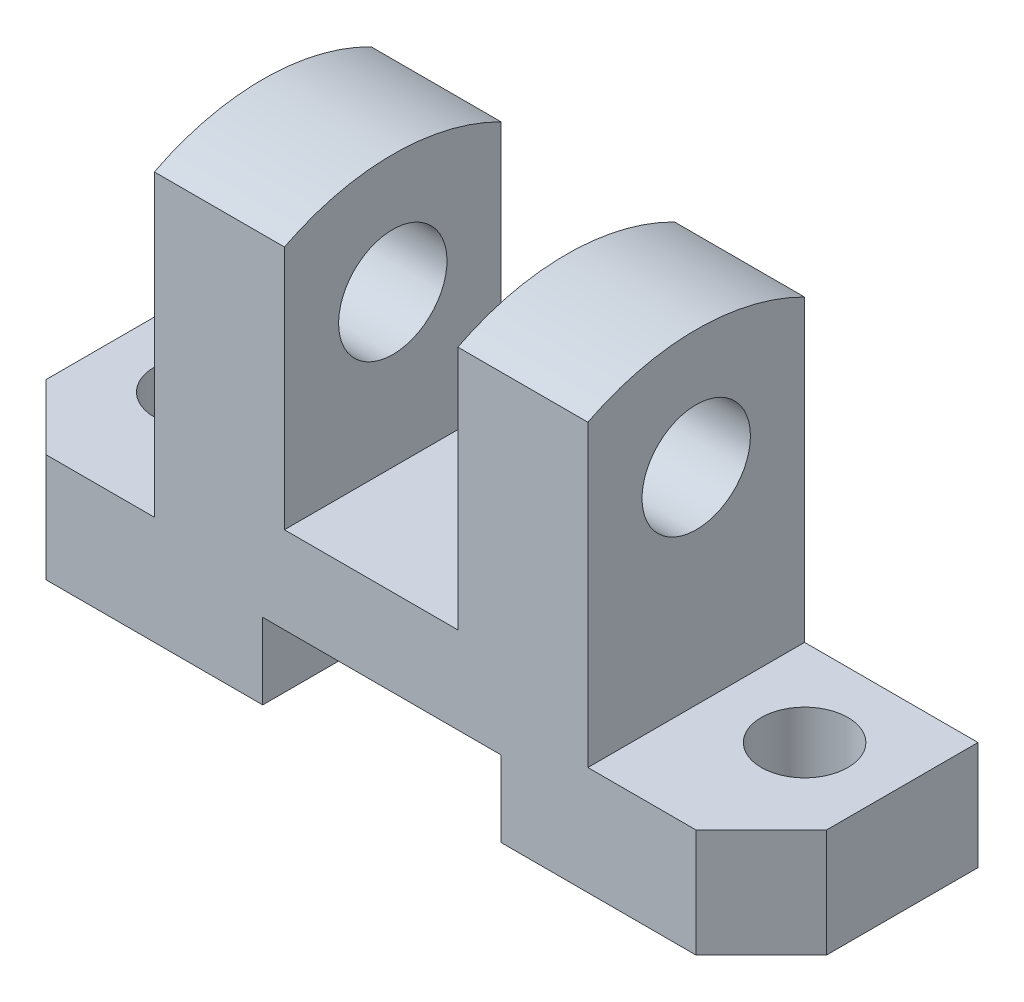
SolidWorks part; units mm, degrees
material "6063-T6"
ref_plane "Plane1" through (0, 0, 0) normal (0, 0, 1) x (1, 0, 0)
ref_plane "Plane2" through (0, 0, 0) normal (0, 1, 0) x (1, 0, 0)
ref_plane "Plane3" through (0, 0, 0) normal (1, 0, 0) x (0, 0, -1)
sketch "Esquisse1" plane through (0, 0, 0) normal (0, 0, 1) x (1, 0, 0)
  line L1 (0, 0) -> (114.3, 0)
  line L2 (0, 0) -> (0, 63.5)
  line L3 (0, 63.5) -> (114.3, 63.5)
  line L4 (114.3, 0) -> (114.3, 63.5)
  dimension "D1" = 114.3
  dimension "D2" = 63.5
extrude "Base-Extrusion" add sketch "Esquisse1" along normal mid plane 31.75
sketch "Esquisse2" plane through (0, 0, 15.875) normal (0, 0, 1) x (1, 0, 0)
  line L0 (114.3, 63.5) -> (0, 63.5) construction
  line L1 (25.4, 63.5) -> (0, 63.5)
  line L2 (25.4, 63.5) -> (25.4, 15.875)
  line L3 (25.4, 15.875) -> (0, 15.875)
  line L4 (0, 63.5) -> (0, 15.875)
  line L5 (0, 63.5) -> (0, 0) construction
  line L6 (0, 0) -> (114.3, 0) construction
  line L7 (114.3, 63.5) -> (88.9, 63.5)
  line L8 (114.3, 63.5) -> (114.3, 15.875)
  line L9 (114.3, 15.875) -> (88.9, 15.875)
  line L10 (88.9, 63.5) -> (88.9, 15.875)
  line L11 (44.45, 63.5) -> (69.85, 63.5)
  line L12 (44.45, 63.5) -> (44.45, 23.8125)
  line L13 (44.45, 23.8125) -> (69.85, 23.8125)
  line L14 (69.85, 63.5) -> (69.85, 23.8125)
  line L15 (41.275, 0) -> (76.2, 0)
  line L16 (41.275, 0) -> (41.275, 11.1125)
  line L17 (41.275, 11.1125) -> (76.2, 11.1125)
  line L18 (76.2, 0) -> (76.2, 11.1125)
  line L19 (114.3, 0) -> (114.3, 63.5) construction
  dimension "D1" = 25.4
  dimension "D2" = 19.05
  dimension "D3" = 25.4
  dimension "D4" = 19.05
  dimension "D5" = 34.925
  dimension "D6" = 11.1125
  dimension "D7" = 12.7
  dimension "D8" = 38.1
  dimension "D9" = 15.875
extrude "Enlèv. mat.-Extru.1" cut sketch "Esquisse2" against normal through all
sketch "Esquisse3" plane through (88.9, 0, 0) normal (1, 0, 0) x (0, 0, -1)
  line L0 (-34.925, 68.575) -> (-34.925, 28.575)
  line L1 (-34.925, 68.575) -> (34.925, 68.575)
  line L2 (34.925, 68.575) -> (34.925, 28.575)
  line L3 (-15.875, 63.5) -> (-15.875, 15.875) construction
  line L4 (15.875, 63.5) -> (-15.875, 63.5) construction
  arc A0 (-34.925, 28.575) -> (34.925, 28.575) centre (0, 28.575) cw
  dimension "D1" = 34.925
  dimension "D2" = 15.875
  dimension "D3" = 34.925
  dimension "D4" = 40
extrude "Enlèv. mat.-Extru.2" cut sketch "Esquisse3" against normal through all
chamfer "Chanfrein1" distance 9.525 angle 45 2 edges at (114.3, 7.9375, 15.875) (0, 7.9375, 15.875)
hole_wizard "Diamètre du perçage 1/2 (0.5)1" positions "Esquisse4" profile "Esquisse5" hole size "1/2" standard "Ansi Inch" end condition through all
sketch "Esquisse4" plane through (0, 15.875, 0) normal (0, 1, 0) x (1, 0, 0)
  line L0 (0, 15.875) -> (25.4, 15.875) construction
  line L1 (114.3, 15.875) -> (114.3, -6.35) construction
  line L2 (0, 15.875) -> (0, -6.35) construction
  point P0 (101.6, 3.175)
  point P2 (12.7, 3.175)
  point P11 (114.3, 4.7625)
  dimension "D1" = 12.7
  dimension "D2" = 12.7
  dimension "D3" = 12.7
sketch "Esquisse5" plane through (101.6, 15.875, -3.175) normal (1, 0, 0) x (0, 0, 1)
  line L0 (0, 0) -> (0, 15.875)
  line L1 (0, 15.875) -> (6.35, 15.875)
  line L2 (6.35, 15.875) -> (6.35, 0)
  line L5 (6.35, 0) -> (0, 0)
  line L11 (0, -6.35) -> (0, 107.95) construction
  dimension "Diamètre du perçage jusqu'au prochain" = 12.7
  dimension "Profondeur du perçage jusqu'au prochain" = 15.875
hole_wizard "Diamètre du perçage 5/8 (0.625)1" positions "Esquisse6" profile "Esquisse7" hole size "5/8" standard "Ansi Inch" end condition through all
sketch "Esquisse6" plane through (88.9, 0, 0) normal (1, 0, 0) x (0, 0, -1)
  line L0 (-6.35, 0) -> (15.875, 0) construction
  point P0 (0, 46.0375)
  dimension "D1" = 46.0375
sketch "Esquisse7" plane through (88.9, 46.0375, 0) normal (0, 1, 0) x (0, 0, -1)
  line L0 (0, 0) -> (0, 88.9)
  line L1 (0, 88.9) -> (7.9375, 88.9)
  line L2 (7.9375, 88.9) -> (7.9375, 0)
  line L5 (7.9375, 0) -> (0, 0)
  line L11 (0, -6.35) -> (0, 107.95) construction
  dimension "Diamètre du perçage jusqu'au prochain" = 15.875
  dimension "Profondeur du perçage jusqu'au prochain" = 88.9
